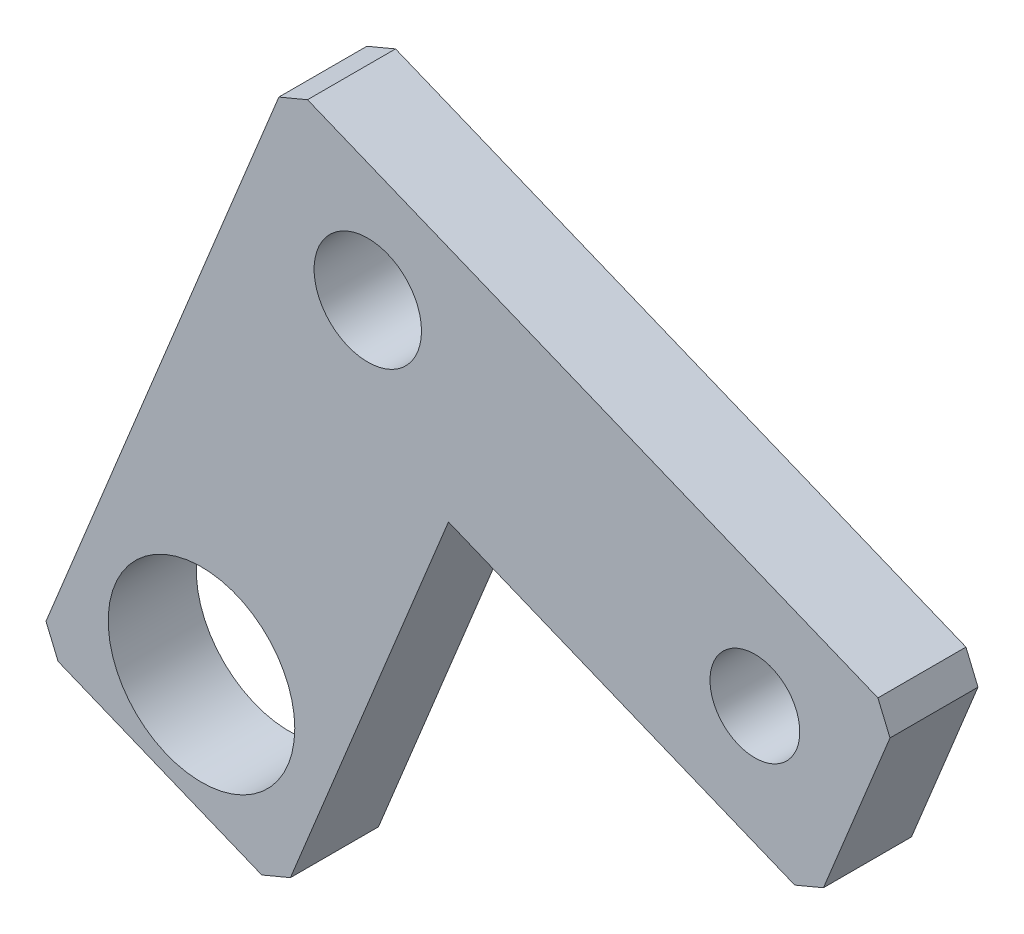
SolidWorks part; units mm, degrees
ref_plane "前基準面" through (0, 0, 0) normal (0, 0, 1) x (1, 0, 0)
ref_plane "上基準面" through (0, 0, 0) normal (0, 1, 0) x (1, 0, 0)
ref_plane "右基準面" through (0, 0, 0) normal (1, 0, 0) x (0, 0, -1)
sketch "草圖1" plane through (0, 0, 0) normal (0, 0, 1) x (1, 0, 0)
  line L0 (-42.6847, 14.9509) -> (26.7532, -13.3931)
  line L5 (26.7532, -13.3931) -> (17.3052, -36.5391)
  line L6 (17.3052, -36.5391) -> (-24.3576, -19.5327)
  line L7 (-24.3576, -19.5327) -> (-43.2535, -65.8246)
  line L8 (-43.2535, -65.8246) -> (-71.0287, -54.487)
  line L9 (-71.0287, -54.487) -> (-42.6847, 14.9509)
  line L10 (22.0292, -24.9661) -> (-47.4087, 3.3779) construction
  line L11 (-57.1411, -60.1558) -> (-28.7971, 9.2821) construction
  circle A0 centre (10.4562, -20.2421) radius 5.1
  circle A1 centre (-33.5211, -2.2909) radius 6.1
  circle A2 centre (-52.4171, -48.5828) radius 10.6
  point P12 (-33.5211, -2.2909)
  dimension "D5" = 10.2
  dimension "D8" = 12.2
  dimension "D9" = 21.2
  dimension "D1" = 25
  dimension "D2" = 30
  dimension "D3" = 75
  dimension "D4" = 75
  dimension "D6" = 12.5
  dimension "D7" = 12.5
  dimension "D10" = 12.5
extrude "填料-伸長1" add sketch "草圖1" against normal blind 10
chamfer "導角1" distance 2.5 angle 45 5 edges at (-43.2535, -65.8246, -5) (17.3052, -36.5391, -5) (26.7532, -13.3931, -5) (-71.0287, -54.487, -5) (-42.6847, 14.9509, -5)
